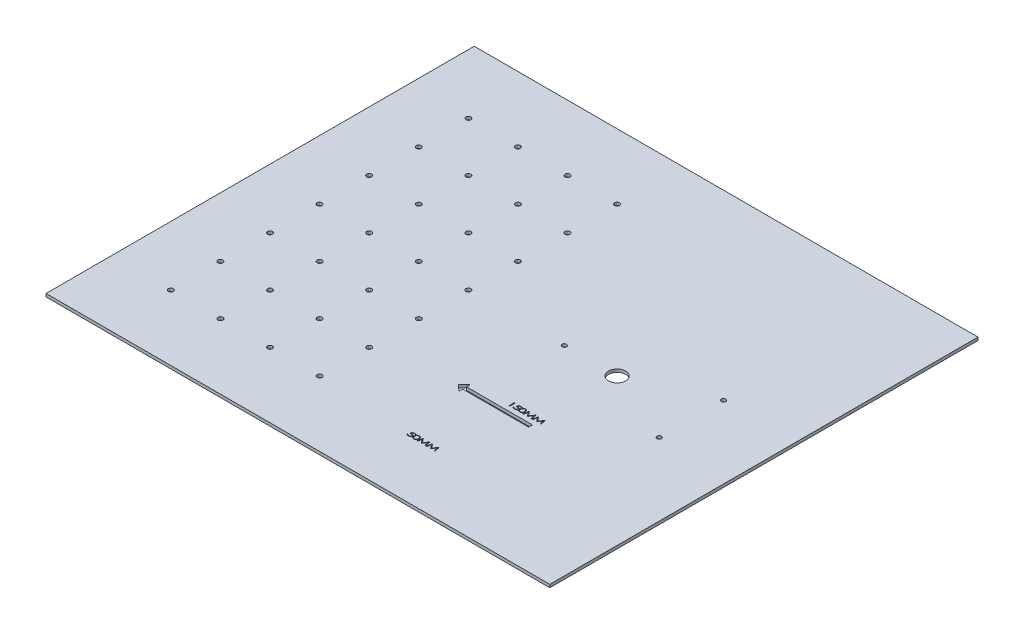
SolidWorks part; units mm, degrees
ref_plane "Plan de face" through (0, 0, 0) normal (0, 0, 1) x (1, 0, 0)
ref_plane "Plan de dessus" through (0, 0, 0) normal (0, 1, 0) x (1, 0, 0)
ref_plane "Plan de droite" through (0, 0, 0) normal (1, 0, 0) x (0, 0, -1)
sketch "Sketch1" plane through (0, 0, 0) normal (0, 1, 0) x (1, 0, 0)
  line L1 (-254, -215.9) -> (254, -215.9)
  line L2 (-254, -215.9) -> (-254, 215.9)
  line L3 (-254, 215.9) -> (254, 215.9)
  line L4 (254, -215.9) -> (254, 215.9)
  line L5 (-254, -215.9) -> (254, 215.9) construction
  line L6 (-254, 215.9) -> (254, -215.9) construction
  point P0 (0, 0)
  dimension "D1" = 508
  dimension "D2" = 431.8
extrude "Boss-Extrude1" add sketch "Sketch1" along normal blind 3 contours L3 L4 L1 L2
sketch "Sketch3" plane through (0, 3, 0) normal (0, 1, 0) x (1, 0, 0)
  circle A3 centre (180.9361, -32.4307) radius 2.25 construction
  circle A4 centre (180.9361, 32.4307) radius 2.25 construction
  circle A5 centre (52.8129, 0) radius 2.25 construction
  circle A6 centre (180.9361, -32.4307) radius 2.25
  circle A7 centre (180.9361, 32.4307) radius 2.25
  circle A8 centre (52.8129, 0) radius 2.25
  circle A10 centre (106, 0) radius 8.65 construction
  circle A11 centre (106, 0) radius 8.65
extrude "Cut-Extrude1" cut sketch "Sketch3" against normal through all
sketch "Sketch4" plane through (0, 3, 0) normal (0, 1, 0) x (1, 0, 0)
  circle A0 centre (-44, 0) radius 2.5
  point P2 (0, 0)
  dimension "D1" = 5
  dimension "D2" = 150
extrude "Cut-Extrude2" cut sketch "Sketch4" against normal through all
pattern_linear "LPattern1" count 4 spacing 50 along (0, 0, -1) count 4 spacing 50 along (-1, 0, 0) of "Cut-Extrude2"
mirror "Mirror1" about plane through (0, 0, 0) normal (0, 0, 1) of "LPattern1"
sketch "Sketch5" plane through (0, 3, 0) normal (0, 1, 0) x (1, 0, 0)
  line L0 (106, -85.4347) -> (39.5876, -85.4347)
  line L1 (39.5876, -85.4347) -> (39.5876, -81.7819)
  line L2 (39.5876, -81.7819) -> (33.1815, -87.3622)
  line L3 (33.1815, -87.3622) -> (30.6369, -87.3622) construction
  line L4 (106, -89.2897) -> (39.5876, -89.2897)
  line L5 (39.5876, -92.9426) -> (33.1815, -87.3622)
  line L6 (39.5876, -89.2897) -> (39.5876, -92.9426)
  line L7 (106, -85.4347) -> (106, -89.2897)
  text T0 "150MM" font "Century Gothic" height in points 20
  text T1 "50MM" font "Century Gothic" height in points 20
  point P7 (0, 0)
  point P9 (0, 0)
  point P10 (36.8374, -157.1745)
  point P11 (50.2257, -157.4425)
extrude "Cut-Extrude3" cut sketch "Sketch5" against normal through all
